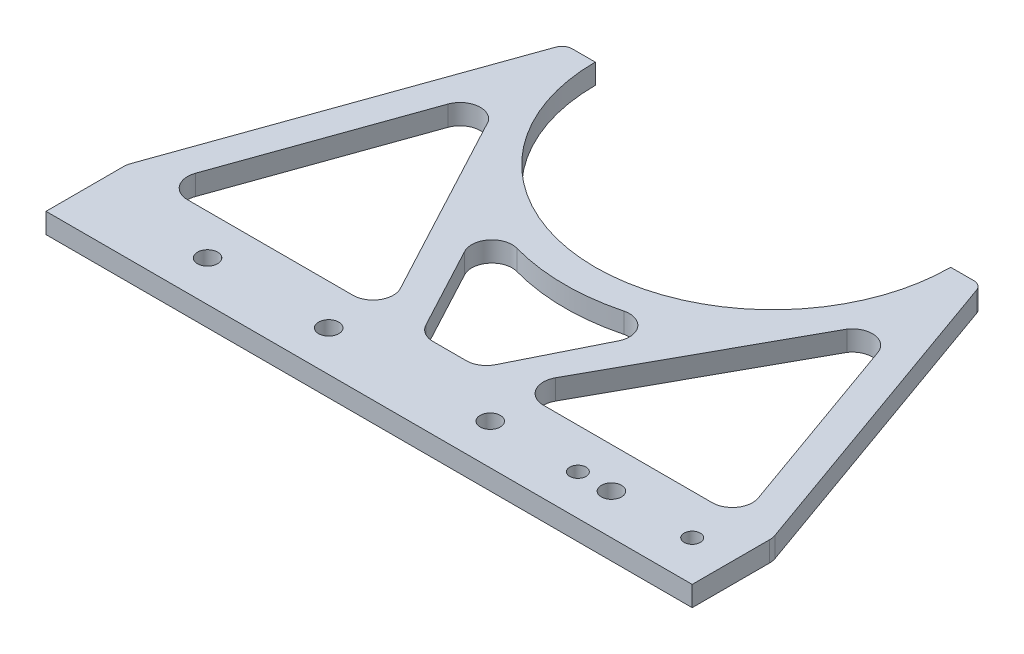
SolidWorks part; units mm, degrees
ref_plane "Front Plane" through (0, 0, 0) normal (0, 0, 1) x (1, 0, 0)
ref_plane "Top Plane" through (0, 0, 0) normal (0, 1, 0) x (1, 0, 0)
ref_plane "Right Plane" through (0, 0, 0) normal (1, 0, 0) x (0, 0, -1)
sketch "Sketch1" plane through (0, 0, 0) normal (0, 1, 0) x (1, 0, 0)
  line L0 (-55.88, 63.5) -> (-65.405, 63.5)
  line L1 (-101.6, 63.5) -> (-55.88, 63.5) construction
  line L2 (-101.6, 63.5) -> (-101.6, -63.5) construction
  line L3 (-101.6, -63.5) -> (101.6, -63.5)
  line L4 (101.6, 63.5) -> (101.6, -63.5) construction
  line L5 (55.88, 63.5) -> (65.405, 63.5)
  line L6 (-65.405, 63.5) -> (-101.2318, -37.0663)
  line L7 (0, 119.38) -> (0, 50000) construction
  line L8 (55.88, 63.5) -> (101.6, 63.5) construction
  line L9 (-101.6, -39.1973) -> (-101.6, -63.5)
  line L10 (101.6, -63.5) -> (101.6, -39.1973)
  line L11 (101.2318, -37.0663) -> (65.405, 63.5)
  line L12 (-82.4855, -38.1) -> (-30.4925, -38.1)
  line L13 (-67.621, 28.897) -> (-88.4673, -29.619)
  line L14 (88.4673, -29.619) -> (67.621, 28.897)
  line L15 (-56.4324, 60.3035) -> (-92.6274, -41.2965) construction
  line L16 (92.6274, -41.2965) -> (56.4324, 60.3035) construction
  line L17 (-24.8906, -28.7596) -> (-57.6986, 32.6993)
  line L18 (0, 22.8283) -> (0, -93.9069) construction
  line L19 (-10.9009, -34.7404) -> (-24.8462, -8.6166)
  line L20 (-11.2649, -34.0585) -> (-49.2959, 37.1849) construction
  line L21 (10.8591, -34.5773) -> (23.6826, -8.7888)
  line L22 (23.8626, -28.6846) -> (57.6986, 32.6993)
  line L23 (-19.6676, -38.544) -> (-57.6986, 32.6993) construction
  line L24 (-5.299, -38.1) -> (5.1732, -38.1)
  line L25 (29.4237, -38.1) -> (82.4855, -38.1)
  line L26 (-65.405, 63.5) -> (-101.6, -38.1) construction
  line L27 (101.6, -38.1) -> (65.405, 63.5) construction
  arc A0 (-55.88, 63.5) -> (55.88, 63.5) centre (0, 63.5) ccw
  circle A1 centre (-63.5, -50.8) radius 3.175
  circle A2 centre (63.5, -50.8) radius 3.175
  arc A3 (-17.5414, 0.4912) -> (16.4041, 0.1855) centre (0, 63.5) ccw
  arc A4 (-65.405, 63.5) -> (65.405, 63.5) centre (0, 63.5) ccw construction
  arc A5 (-56.1844, 30.0168) -> (-67.621, 28.897) centre (-61.6392, 26.766) ccw
  arc A6 (-24.8906, -28.7596) -> (-30.4925, -38.1) centre (-30.4925, -31.75) cw
  arc A7 (-82.4855, -38.1) -> (-88.4673, -29.619) centre (-82.4855, -31.75) cw
  arc A8 (-17.5414, 0.4912) -> (-24.8462, -8.6166) centre (-19.2444, -5.6262) ccw
  arc A9 (16.4041, 0.1855) -> (23.6826, -8.7888) centre (17.9967, -5.9615) cw
  arc A10 (-10.9009, -34.7404) -> (-5.299, -38.1) centre (-5.299, -31.75) ccw
  arc A11 (5.1732, -38.1) -> (10.8591, -34.5773) centre (5.1732, -31.75) ccw
  arc A12 (56.1844, 30.0168) -> (57.6986, 32.6993) centre (0, 63.5) cw construction
  arc A13 (56.1844, 30.0168) -> (67.621, 28.897) centre (61.6392, 26.766) cw
  arc A14 (23.8626, -28.6846) -> (29.4237, -38.1) centre (29.4237, -31.75) ccw
  arc A15 (82.4855, -38.1) -> (88.4673, -29.619) centre (82.4855, -31.75) ccw
  arc A16 (-57.6986, 32.6993) -> (-56.1844, 30.0168) centre (0, 63.5) cw construction
  arc A17 (16.4041, 0.1855) -> (-17.5414, 0.4912) centre (0, 63.5) cw
  arc A18 (-101.6, -39.1973) -> (-101.2318, -37.0663) centre (-95.25, -39.1973) cw
  arc A19 (101.6, -39.1973) -> (101.2318, -37.0663) centre (95.25, -39.1973) ccw
  circle A20 centre (-25.4, -50.8) radius 3.175
  circle A21 centre (25.4, -50.8) radius 3.175
  point P0 (0, 0)
  point P40 (-9.1074, -38.1)
  point P57 (9.1074, -38.1)
  point P64 (91.4886, -38.1)
  dimension "D3" = 6.35
  dimension "D6" = 6.35
  dimension "D9" = 9.525
  dimension "D15" = 6.35
  dimension "D16" = 6.35
  dimension "D17" = 6.35
  dimension "D14" = 6.35
  dimension "D18" = 6.35
  dimension "D19" = 6.35
  dimension "D20" = 6.35
  dimension "D21" = 6.35
  dimension "D22" = 6.35
  dimension "D23" = 6.35
  dimension "D24" = 6.35
  dimension "D1" = 127
  dimension "D2" = 203.2
  dimension "D4" = 12.7
  dimension "D5" = 38.1
  dimension "D7" = 12.7
  dimension "D8" = 38.1
  dimension "D10" = 25.4
  dimension "D25" = 76.2
  dimension "D26" = 76.2
  dimension "D11" = 9.525
  dimension "D12" = 9.525
  dimension "D13" = 9.525
extrude "Boss-Extrude1" add sketch "Sketch1" along normal blind 6.35
fillet "Fillet1" radius 3.175 2 edges at (65.405, 3.175, -63.5) (-65.405, 3.175, -63.5)
sketch "Sketch2" plane through (0, 6.35, 0) normal (0, 1, 0) x (1, 0, 0)
  line L0 (101.6, -63.5) -> (101.6, -39.1973) construction
  line L1 (-101.6, -63.5) -> (101.6, -63.5) construction
  point P0 (88.9, -50.8)
  point P1 (52.959, -50.8)
  point P6 (0, 0)
  dimension "D1" = 12.7
  dimension "D2" = 12.7
  dimension "D3" = 35.941
hole_wizard "#10 Clearance Hole1" positions "Sketch3" profile "Sketch4" hole size "#10" standard "ANSI Inch" end condition through all
sketch "Sketch3" plane through (0, 6.35, 0) normal (0, 1, 0) x (1, 0, 0)
  point P0 (52.959, -50.8)
  point P3 (88.9, -50.8)
sketch "Sketch4" plane through (52.959, 6.35, 50.8) normal (1, 0, 0) x (0, 0, 1)
  line L0 (0, 0) -> (0, 6.35)
  line L1 (0, 6.35) -> (2.5527, 6.35)
  line L2 (2.5527, 6.35) -> (2.5527, 0)
  line L5 (2.5527, 0) -> (0, 0)
  line L11 (0, -6.35) -> (0, 107.95) construction
  dimension "Thru Hole Dia." = 5.1054
  dimension "Thru Hole Depth" = 6.35
